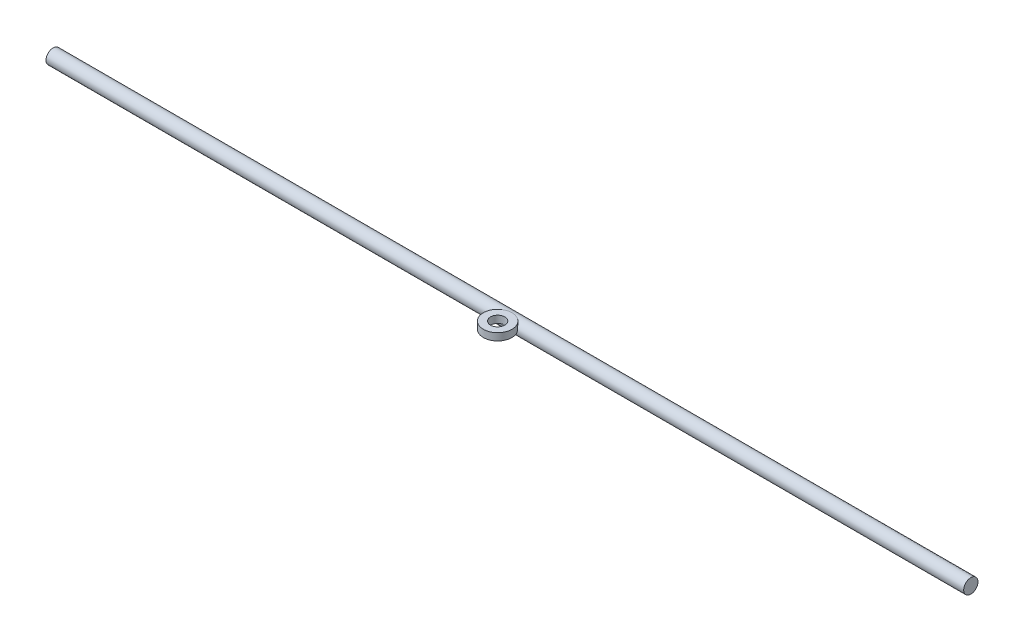
SolidWorks part; units mm, degrees
ref_plane "Plan de face" through (0, 0, 0) normal (0, 0, 1) x (1, 0, 0)
ref_plane "Plan de dessus" through (0, 0, 0) normal (0, 1, 0) x (1, 0, 0)
ref_plane "Plan de droite" through (0, 0, 0) normal (1, 0, 0) x (0, 0, -1)
sketch "Esquisse1" plane through (0, 0, 0) normal (0, 0, 1) x (1, 0, 0)
  line L0 (-320, 0) -> (320, 0)
  dimension "D1" = 640
sweep "Balayage1" add path "Esquisse1" circular profile diameter 10 parameters "D3"=10
sketch "Esquisse2" plane through (0, 0, 0) normal (0, 1, 0) x (1, 0, 0)
  line L0 (-320, -5) -> (320, -5) construction
  circle A0 centre (0, -10) radius 5
  circle A1 centre (0, -10) radius 10
  dimension "D1" = 10
  dimension "D2" = 5
extrude "Boss.-Extru.1" add sketch "Esquisse2" along normal blind 5
